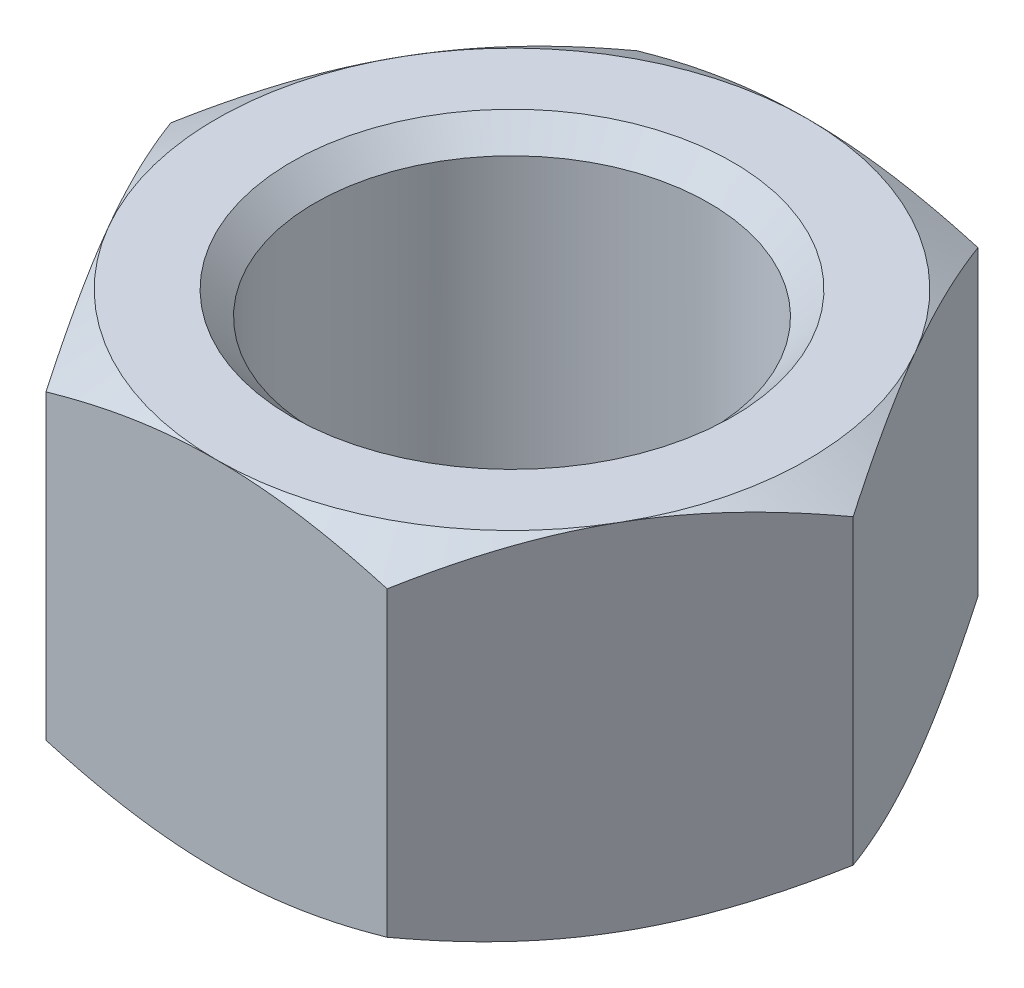
SolidWorks part; units mm, degrees
material "普通碳钢"
ref_plane "前视基准面" through (0, 0, 0) normal (0, 0, 1) x (1, 0, 0)
ref_plane "上视基准面" through (0, 0, 0) normal (0, 1, 0) x (1, 0, 0)
ref_plane "右视基准面" through (0, 0, 0) normal (1, 0, 0) x (0, 0, -1)
sketch "草图1" plane through (0, 0, 0) normal (0, 1, 0) x (1, 0, 0)
  line L1 (17.3205, 0) -> (8.6603, 15)
  line L2 (8.6603, 15) -> (-8.6603, 15)
  line L3 (-8.6603, 15) -> (-17.3205, 0)
  line L4 (-17.3205, 0) -> (-8.6603, -15)
  line L5 (-8.6603, -15) -> (8.6603, -15)
  line L6 (8.6603, -15) -> (17.3205, 0)
  circle A0 centre (0, 0) radius 15 construction
  dimension "D1" = 30
extrude "凸台-拉伸1" add sketch "草图1" along normal mid plane 18
sketch "草图2" plane through (0, 9, 0) normal (0, 1, 0) x (1, 0, 0)
  circle A0 centre (0, 0) radius 10
  dimension "D1" = 20
extrude "切除-拉伸1" cut sketch "草图2" against normal through all
chamfer "倒角1" distance 1.2 angle 45 2 edges at (0, 9, 10) (0, -9, 10)
sketch "草图3" plane through (0, 0, 0) normal (0, 0, 1) x (1, 0, 0)
  line L0 (0, 9) -> (0, -9) construction
  line L1 (-8.6603, 9) -> (8.6603, 9) construction
  line L2 (-8.6603, -9) -> (8.6603, -9) construction
  line L3 (17.3205, 9) -> (15, 9)
  line L4 (8.6603, 9) -> (17.3205, 9) construction
  line L5 (15, 9) -> (17.3205, 7.6603)
  line L6 (17.3205, 9) -> (17.3205, -9) construction
  line L7 (17.3205, 7.6603) -> (17.3205, 9)
  dimension "D1" = 30
  dimension "D2" = 30
revolve "切除-旋转1" cut sketch "草图3" angle 360 about L0
mirror "镜向1" about plane through (0, 0, 0) normal (0, 1, 0) of "切除-旋转1"
